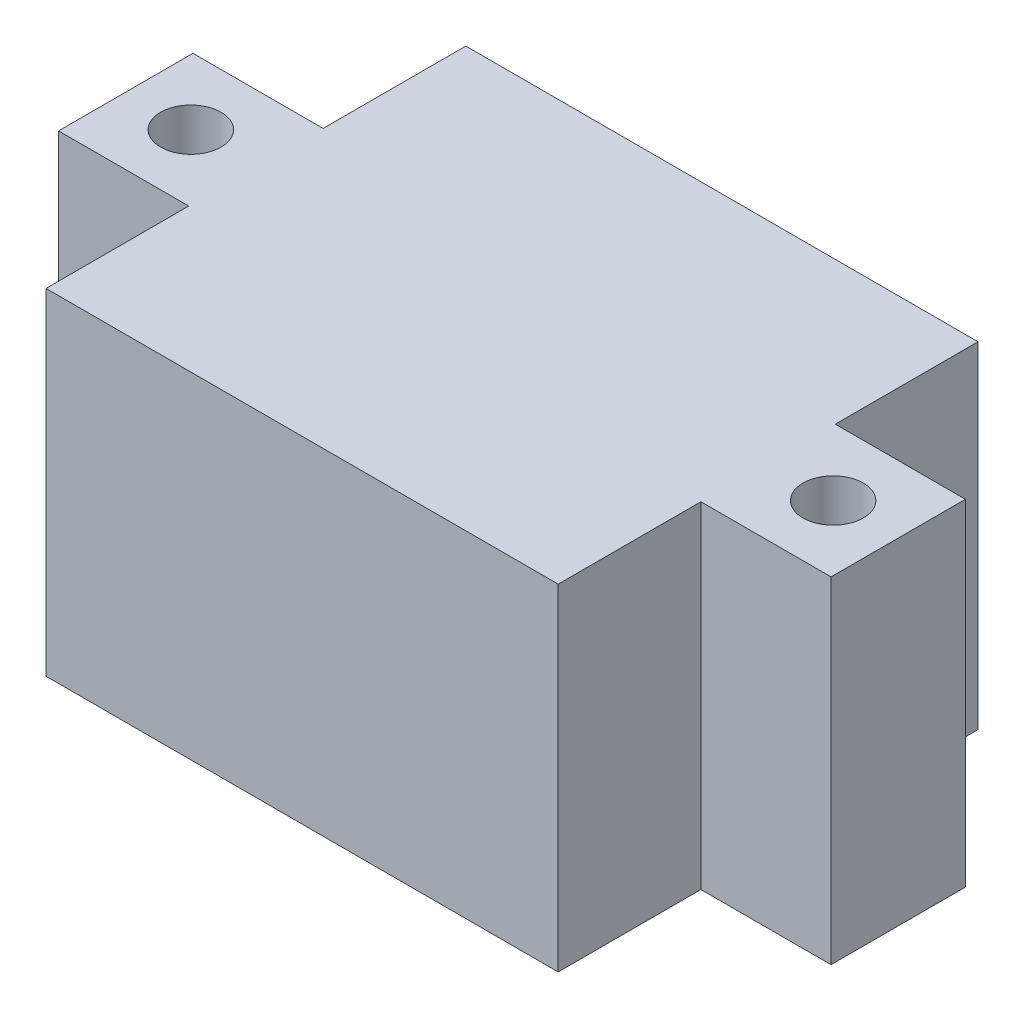
SolidWorks part; units mm, degrees
ref_plane "Plan de face" through (0, 0, 0) normal (0, 0, 1) x (1, 0, 0)
ref_plane "Plan de dessus" through (0, 0, 0) normal (0, 1, 0) x (1, 0, 0)
ref_plane "Plan de droite" through (0, 0, 0) normal (1, 0, 0) x (0, 0, -1)
sketch "Esquisse1" plane through (0, 0, 0) normal (0, 1, 0) x (1, 0, 0)
  line L1 (-15.25, -12.5) -> (15.25, -12.5)
  line L2 (-23, -4.0013) -> (-23, 4.0013)
  line L3 (-15.25, 12.5) -> (15.25, 12.5)
  line L4 (23, -4.0013) -> (23, 4.0013)
  line L9 (23, 4.0013) -> (15.25, 4.0013)
  line L10 (15.25, 12.5) -> (15.25, 4.0013)
  line L13 (-23, 4.0013) -> (-15.25, 4.0013)
  line L14 (-15.25, 12.5) -> (-15.25, 4.0013)
  line L17 (-23, -4.0013) -> (-15.25, -4.0013)
  line L18 (-15.25, -12.5) -> (-15.25, -4.0013)
  line L21 (23, -4.0013) -> (15.25, -4.0013)
  line L22 (15.25, -12.5) -> (15.25, -4.0013)
  point P0 (0, 0)
  point P1 (0, 12.5)
  point P2 (23, 0)
  dimension "D1" = 8.0027
  dimension "D3" = 7.75
  dimension "D4" = 8.4987
  dimension "D5" = 30.5
extrude "Boss.-Extru.1" add sketch "Esquisse1" along normal blind 20 contours L3 L10 L9 L4 L21 L22 L1 L18 L17 L2 L13 L14
hole_wizard "Dégagement M31" positions "Esquisse2" profile "Esquisse3" hole size "M3" standard "Ansi Metric" end condition through all
sketch "Esquisse2" plane through (0, 20, 0) normal (0, 1, 0) x (1, 0, 0)
  line L0 (-23, 4.0013) -> (-15.25, 4.0013) construction
  line L1 (-23, -4.0013) -> (-23, 4.0013) construction
  line L2 (23, 4.0013) -> (15.25, 4.0013) construction
  point P0 (-19.125, 0)
  point P2 (19.125, 0)
  point P7 (-19.125, 4.0013)
  point P10 (-23, 0)
  point P11 (0, 0)
  point P12 (0, 0)
  point P15 (19.125, 4.0013)
sketch "Esquisse3" plane through (-19.125, 20, 0) normal (1, 0, 0) x (0, 0, 1)
  line L0 (0, 0) -> (0, 20)
  line L1 (0, 20) -> (1.8, 20)
  line L2 (1.8, 20) -> (1.8, 0)
  line L5 (1.8, 0) -> (0, 0)
  line L11 (0, -6.35) -> (0, 107.95) construction
  dimension "Diamètre du perçage jusqu'au prochain" = 3.6
  dimension "Profondeur du perçage jusqu'au prochain" = 20
